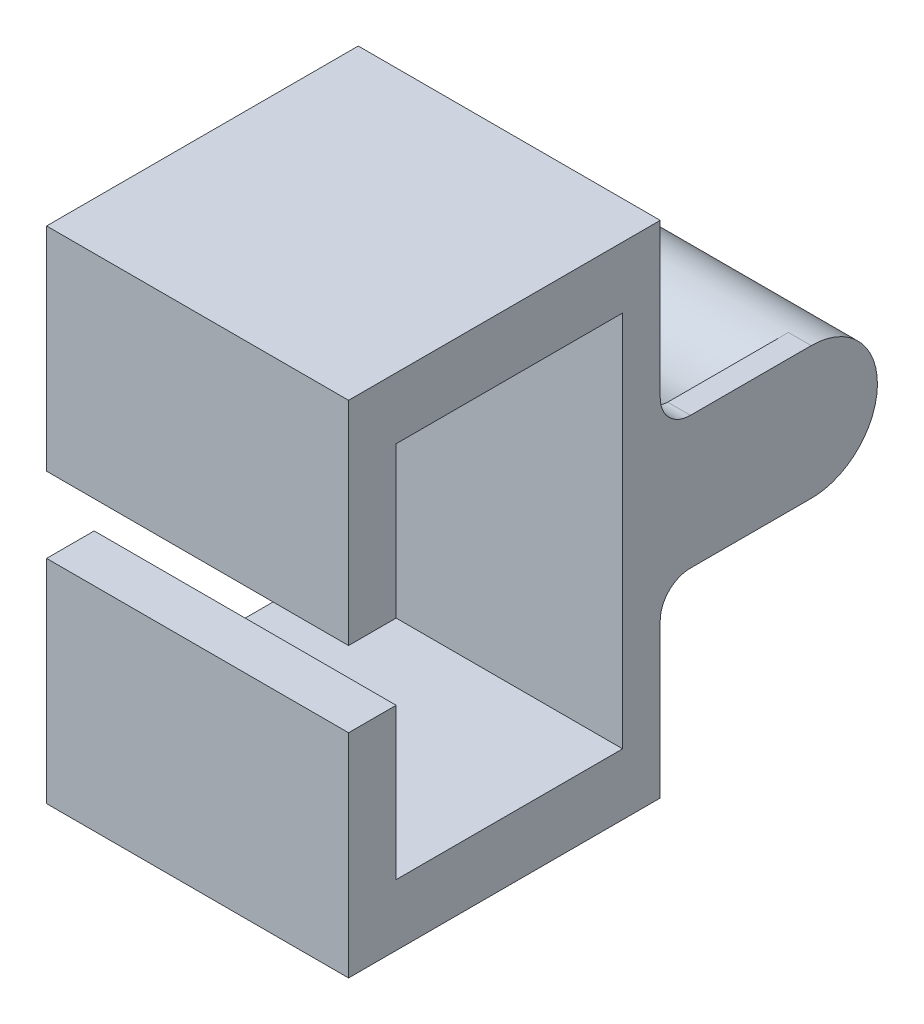
SolidWorks part; units mm, degrees
material "ASTM A36 Steel"
ref_plane "Front Plane" through (0, 0, 0) normal (1, 0, 0) x (0, 1, 0)
ref_plane "Top Plane" through (0, 0, 0) normal (0, 0, 1) x (0, 1, 0)
ref_plane "Right Plane" through (0, 0, 0) normal (0, 1, 0) x (-1, 0, 0)
sketch "Sketch1" plane through (0, 0, 0) normal (1, 0, 0) x (0, 1, 0)
  circle A0 centre (0, 0) radius 11.1361
  dimension "D1" = 22.2722
extrude "Boss-Extrude1" add sketch "Sketch1" along normal blind 50.8 contours A0
sketch "Sketch2" plane through (0, 0, 0) normal (-1, 0, 0) x (0, -1, 0)
  line L0 (12.2437, 0) -> (-12.2437, 0) construction
  line L1 (-11.1361, 0) -> (11.1252, 0)
  line L2 (-11.1361, 0) -> (-11.1361, 25.4)
  line L3 (-11.1361, 25.4) -> (11.1252, 25.4)
  line L4 (11.1252, 0) -> (11.1252, 25.4)
  circle A0 centre (0, 0) radius 11.1361 construction
  dimension "D1" = 25.4
extrude "Boss-Extrude2" add sketch "Sketch2" against normal blind 3.8346 contours L2 L3 L4 L1
sketch "Sketch3" plane through (0, 0, 0) normal (1, 0, 0) x (0, 1, 0)
  line L0 (0, -27.94) -> (0, 27.94) construction
  line L1 (-31.75, 25.4) -> (31.75, 25.4)
  line L2 (-31.75, 25.4) -> (-31.75, 31.7272)
  line L3 (-31.75, 31.7272) -> (31.75, 31.7272)
  line L4 (31.75, 25.4) -> (31.75, 31.7272)
  line L5 (11.1361, 25.4) -> (-11.1252, 25.4) construction
  point P4 (0, 25.4)
  dimension "D1" = 63.5
  dimension "D2" = 6.3272
extrude "Boss-Extrude3" add sketch "Sketch3" along normal blind 50.8
sketch "Sketch4" plane through (0, 0, 0) normal (1, 0, 0) x (0, 1, 0)
  line L0 (31.75, 31.7272) -> (-31.75, 31.7272) construction
  line L1 (-31.75, 25.4) -> (-42.0823, 25.4)
  line L2 (-31.75, 25.4) -> (-31.75, 69.8272)
  line L3 (-31.75, 69.8272) -> (-42.0823, 69.8272)
  line L4 (-42.0823, 25.4) -> (-42.0823, 69.8272)
  line L5 (31.75, 25.4) -> (42.0823, 25.4)
  line L6 (31.75, 25.4) -> (31.75, 69.8272)
  line L7 (31.75, 69.8272) -> (42.0823, 69.8272)
  line L8 (42.0823, 25.4) -> (42.0823, 69.8272)
  dimension "D1" = 10.3323
  dimension "D2" = 38.1
extrude "Boss-Extrude4" add sketch "Sketch4" along normal blind 50.8
sketch "Sketch5" plane through (0, 0, 0) normal (1, 0, 0) x (0, 1, 0)
  line L1 (-42.0823, 69.8272) -> (-6.35, 69.8272)
  line L2 (-42.0823, 69.8272) -> (-42.0823, 77.8306)
  line L3 (-42.0823, 77.8306) -> (-6.35, 77.8306)
  line L4 (-6.35, 69.8272) -> (-6.35, 77.8306)
  line L5 (42.0823, 69.8272) -> (6.35, 69.8272)
  line L6 (42.0823, 69.8272) -> (42.0823, 77.8306)
  line L7 (42.0823, 77.8306) -> (6.35, 77.8306)
  line L8 (6.35, 69.8272) -> (6.35, 77.8306)
  dimension "D1" = 8.0034
  dimension "D2" = 25.4
  dimension "D3" = 12.7
extrude "Boss-Extrude5" add sketch "Sketch5" along normal blind 50.8
sketch "Sketch6" plane through (50.8, 0, 0) normal (1, 0, 0) x (0, 1, 0)
  line L0 (27.94, 0) -> (-27.94, 0) construction
  line L1 (-11.1252, 25.4) -> (11.1361, 25.4)
  line L2 (-11.1252, 25.4) -> (-11.1252, 0)
  line L3 (-11.1252, 0) -> (11.1361, 0)
  line L4 (11.1361, 25.4) -> (11.1361, 0)
  arc A0 (11.1361, 0) -> (-11.1252, 0.4931) centre (0, 0) ccw construction
extrude "Boss-Extrude6" add sketch "Sketch6" against normal blind 3.8346
fillet "Fillet2" radius 5.08 6 edges at (1.9173, 11.1361, 25.4) (48.8827, 11.1361, 25.4) (48.8827, -11.1252, 25.4) (46.9654, 0.0055, 25.4) (3.8346, 0.0055, 25.4) (1.9173, -11.1252, 25.4)
equation "\"SAFETY_FAC\"= 4'Given Safety Factor"
equation "\"LOAD\"= 600'Chosen Applied Load (lbf)"
equation "\"LENGTH_A\"= 1in'Chosen Length for Feature A (in)"
equation "\"STRENGTH\"= 36259.4'ASTM A36 Steel Yield Strenght (psi)"
equation "\"DIAMETER_A\"= 2 * ( ( 4 * \"SAFETY_FAC\" * \"LOAD\" * \"LENGTH_A\" ) / ( PI * \"STRENGTH\" ) ) ^ ( 1 / 3 )'Calculated Diameter of Feature A (in)"
equation "\"THICKNESS_B\"= ( \"LOAD\" * 8 ) / ( \"STRENGTH\" * \"DIAMETER_A\" )'Calculated Thickness of Feature B (in)"
equation "\"LENGTH_C\"= 2.5'Found Length based on Given Rigid T-beam Dimensions (in)"
equation "\"PRIMARY_THICKNESS\"= 2'Chosen Thickness of the primary section (in_"
equation "\"HEIGHT_C\" = ( ( ( 3 * \"LOAD\" * \"LENGTH_C\" * \"SAFETY_FAC\" ) / ( \"PRIMARY_THICKNESS\" * \"STRENGTH\" ) ) ^ ( 1 / 2 ) ) / 2'Calculated Height of Feature C (in)"
equation "\"LOAD_DISTANCE_D\"= \"LENGTH_C\" / 2'Calculated Distance of Load Applied to Feature D (in)"
equation "\"HEIGHT_D\"= 1.5'Found Height based on the GIven Rigid T-beam Dimensions (in)"
equation "\"LENGTH_D\" = ( ( ( 12 * \"LOAD\" * \"LOAD_DISTANCE_D\" * \"SAFETY_FAC\" ) / ( \"HEIGHT_D\" * \"STRENGTH\" ) ) ^ ( 1 / 2 ) ) / 2'Calculated Length of Feature D (in)"
equation "\"LENGTH_E\"= 1'Found Length for Feature E on given Rigid T-Beam Dimensions (in)"
equation "\"HEIGHT_E\"= ( ( 3 * \"LENGTH_E\" * \"LOAD\" * \"SAFETY_FAC\" ) / ( \"PRIMARY_THICKNESS\" * \"STRENGTH\" ) ) ^ ( 1 / 2 )'Calculated height of Feature E (in)"
equation "\"D1@Sketch1\"=\"DIAMETER_A\""
equation "\"D1@Boss-Extrude1\"=\"PRIMARY_THICKNESS\""
equation "\"D1@Boss-Extrude2\"=\"THICKNESS_B\""
equation "\"D1@Sketch3\"=\"LENGTH_C\""
equation "\"D2@Sketch3\"=\"HEIGHT_C\""
equation "\"D1@Boss-Extrude3\"=\"PRIMARY_THICKNESS\""
equation "\"D2@Sketch4\"=\"HEIGHT_D\""
equation "\"D1@Sketch4\"=\"LENGTH_D\""
equation "\"D1@Boss-Extrude4\"=\"PRIMARY_THICKNESS\""
equation "\"D1@Sketch5\"=\"HEIGHT_E\""
equation "\"D2@Sketch5\"=\"LENGTH_E\""
equation "\"D1@Boss-Extrude5\"=\"PRIMARY_THICKNESS\""
equation "\"D1@Boss-Extrude6\"=\"THICKNESS_B\""
